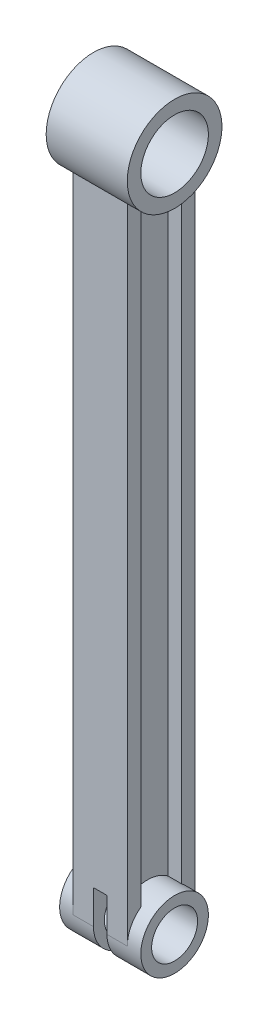
SolidWorks part; units mm, degrees
material "201 Annealed Stainless Steel (SS)"
ref_plane "Front Plane" through (0, 0, 0) normal (0, 0, 1) x (1, 0, 0)
ref_plane "Top Plane" through (0, 0, 0) normal (0, 1, 0) x (1, 0, 0)
ref_plane "Right Plane" through (0, 0, 0) normal (1, 0, 0) x (0, 0, -1)
sketch "Sketch1" plane through (0, 0, 0) normal (0, 1, 0) x (1, 0, 0)
  line L0 (0, 0) -> (0, 15)
  line L2 (10, 15) -> (10, 0)
  line L4 (10, 15) -> (15, 15)
  line L5 (-5, 15) -> (0, 15)
  line L6 (-5, 15) -> (-5, 20)
  line L7 (-5, 20) -> (15, 20)
  line L8 (15, 15) -> (15, 20)
  line L9 (-5, 0) -> (0, 0)
  line L10 (-5, 0) -> (-5, -5)
  line L11 (-5, -5) -> (15, -5)
  line L12 (15, 0) -> (15, -5)
  line L13 (10, 0) -> (15, 0)
  dimension "D1" = 20
  dimension "D2" = 10
  dimension "D3" = 5
  dimension "D4" = 5
  dimension "D5" = 5
  dimension "D6" = 5
  dimension "D7" = 25
extrude "Boss-Extrude1" add sketch "Sketch1" along normal blind 250
sketch "Sketch2" plane through (10, 0, 0) normal (1, 0, 0) x (0, 0, -1)
  line L0 (0, 0) -> (15, 0) construction
  circle A0 centre (7.5, 0) radius 12.5
extrude "Boss-Extrude2" add sketch "Sketch2" along normal blind 10 and the other way blind 20
sketch "Sketch3" plane through (20, 0, 0) normal (1, 0, 0) x (0, 0, -1)
  circle A0 centre (7.5, 0) radius 8.5
extrude "Cut-Extrude1" cut sketch "Sketch3" against normal through all
sketch "Sketch4" plane through (0, 0, 0) normal (-1, 0, 0) x (0, 0, 1)
  line L0 (0, 250) -> (-15, 250) construction
  circle A0 centre (-7.5, 250) radius 17.5
extrude "Boss-Extrude3" add sketch "Sketch4" along normal blind 10 and the other way blind 20
sketch "Sketch5" plane through (20, 0, 0) normal (1, 0, 0) x (0, 0, -1)
  circle A0 centre (7.5, 250) radius 12.5
extrude "Cut-Extrude2" cut sketch "Sketch5" against normal through all
sketch "Sketch6" plane through (0, 0, 0) normal (0, 1, 0) x (1, 0, 0)
  line L0 (-10, 25) -> (-10, -10) construction
  line L1 (2.5, -15) -> (7.5, -15)
  line L2 (2.5, -15) -> (2.5, 25)
  line L3 (2.5, 25) -> (7.5, 25)
  line L4 (7.5, -15) -> (7.5, 25)
  dimension "D1" = 40
  dimension "D2" = 12.5
  dimension "D3" = 5
extrude "Cut-Extrude3" cut sketch "Sketch6" against normal blind 39 from offset 12.5
